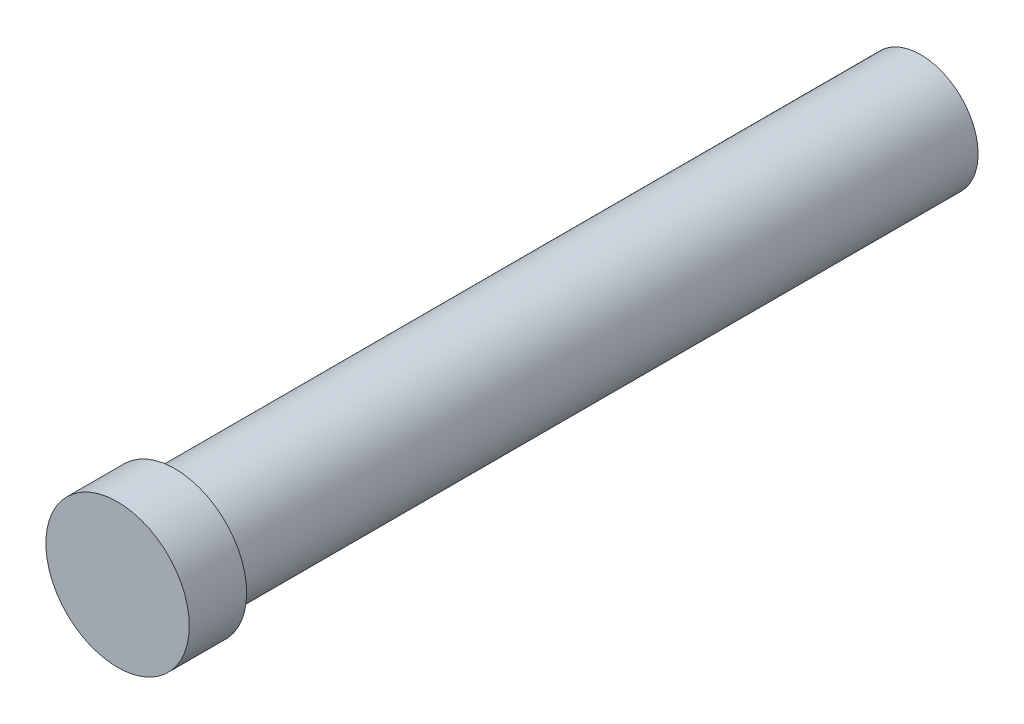
SolidWorks part; units mm, degrees
ref_plane "Front Plane" through (0, 0, 0) normal (0, 0, 1) x (1, 0, 0)
ref_plane "Top Plane" through (0, 0, 0) normal (0, 1, 0) x (1, 0, 0)
ref_plane "Right Plane" through (0, 0, 0) normal (1, 0, 0) x (0, 0, -1)
sketch "Sketch1" plane through (0, 0, 0) normal (0, 0, 1) x (1, 0, 0)
  circle A0 centre (0, 0) radius 1
  dimension "D1" = 2
extrude "Boss-Extrude1" add sketch "Sketch1" along normal blind 13
sketch "Sketch2" plane through (0, 0, 13) normal (0, 0, 1) x (1, 0, 0)
  circle A0 centre (0, 0) radius 1.25
  dimension "D1" = 2.5
extrude "Boss-Extrude2" add sketch "Sketch2" along normal blind 1
